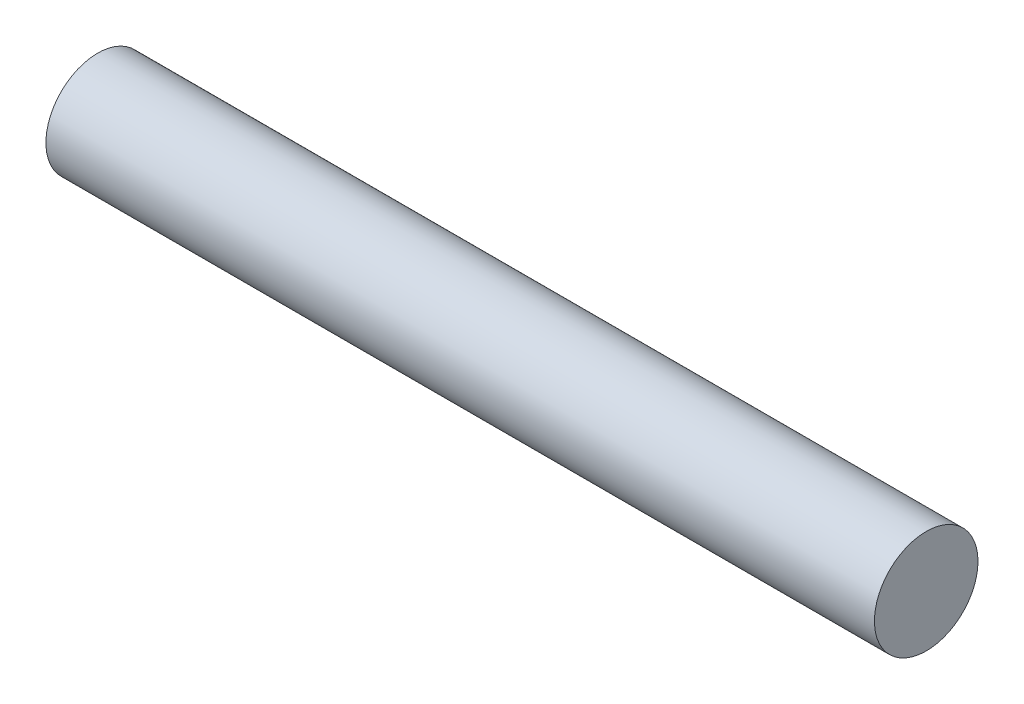
SolidWorks part; units mm, degrees
ref_plane "Front Plane" through (0, 0, 0) normal (0, 0, 1) x (1, 0, 0)
ref_plane "Top Plane" through (0, 0, 0) normal (0, 1, 0) x (1, 0, 0)
ref_plane "Right Plane" through (0, 0, 0) normal (1, 0, 0) x (0, 0, -1)
sketch "Sketch1" plane through (0, 0, 0) normal (1, 0, 0) x (0, 0, -1)
  circle A0 centre (0, 0) radius 3.175
extrude "Boss-Extrude1" add sketch "Sketch1" along normal blind 50.8
